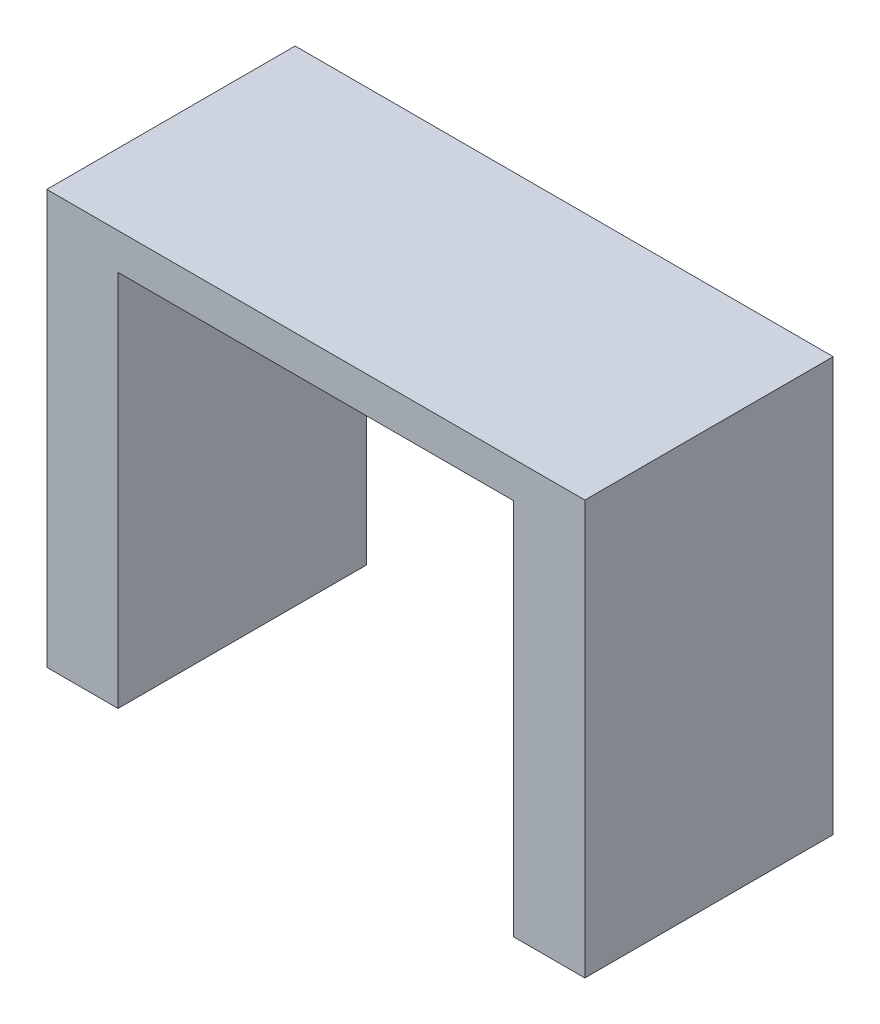
SolidWorks part; units mm, degrees
ref_plane "Alzado" through (0, 0, 0) normal (0, 0, 1) x (1, 0, 0)
ref_plane "Planta" through (0, 0, 0) normal (0, 1, 0) x (1, 0, 0)
ref_plane "Vista lateral" through (0, 0, 0) normal (1, 0, 0) x (0, 0, -1)
sketch "Croquis1" plane through (0, 0, 0) normal (0, 1, 0) x (1, 0, 0)
  line L1 (-6.5, -3) -> (6.5, -3)
  line L2 (-6.5, -3) -> (-6.5, 3)
  line L3 (-6.5, 3) -> (6.5, 3)
  line L4 (6.5, -3) -> (6.5, 3)
  line L5 (-6.5, -3) -> (6.5, 3) construction
  line L6 (-6.5, 3) -> (6.5, -3) construction
  point P0 (0, 0)
  dimension "D1" = 13
  dimension "D2" = 6
extrude "Saliente-Extruir1" add sketch "Croquis1" along normal blind 10
sketch "Croquis2" plane through (0, 0, 3) normal (0, 0, 1) x (1, 0, 0)
  line L0 (0, -3.3) -> (0, 3.3) construction
  line L1 (-4.7787, 9.1244) -> (4.7787, 9.1244)
  line L2 (-4.7787, 9.1244) -> (-4.7787, 0)
  line L3 (-4.7787, 0) -> (4.7787, 0)
  line L4 (4.7787, 9.1244) -> (4.7787, 0)
  line L5 (-4.7787, 9.1244) -> (4.7787, 0) construction
  line L6 (-4.7787, 0) -> (4.7787, 9.1244) construction
  line L7 (3.3, 0) -> (-3.3, 0) construction
  point P0 (0, 4.5622)
extrude "Cortar-Extruir1" cut sketch "Croquis2" against normal blind 10
